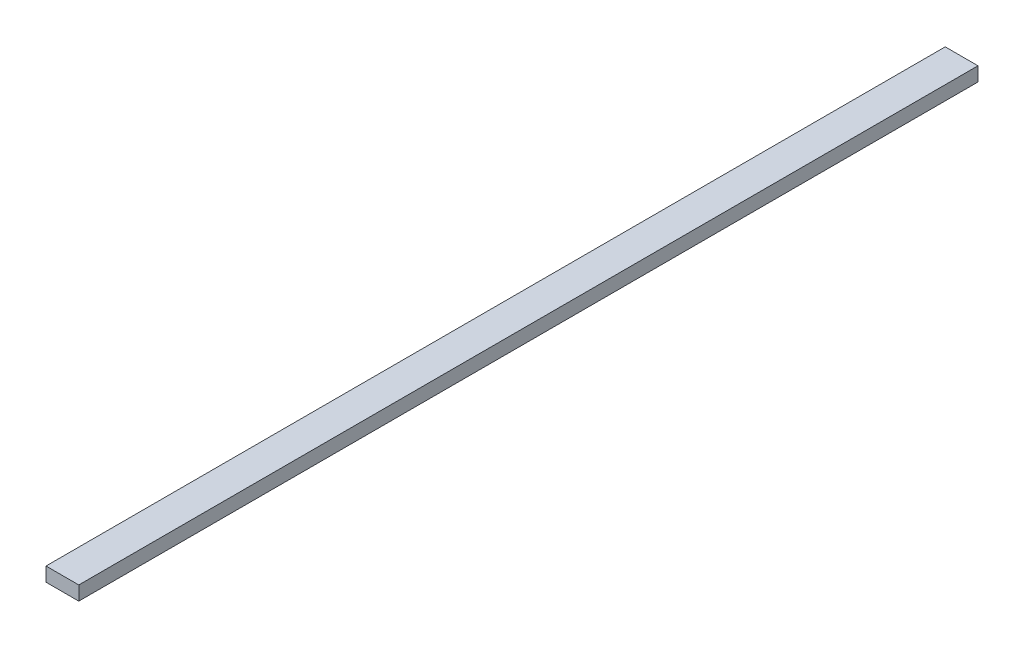
SolidWorks part; units mm, degrees
ref_plane "Front Plane" through (0, 0, 0) normal (0, 0, 1) x (1, 0, 0)
ref_plane "Top Plane" through (0, 0, 0) normal (0, 1, 0) x (1, 0, 0)
ref_plane "Right Plane" through (0, 0, 0) normal (1, 0, 0) x (0, 0, -1)
sketch "Sketch1" plane through (0, 0, 0) normal (0, 0, 1) x (1, 0, 0)
  line L1 (-44.45, -19.05) -> (44.45, -19.05)
  line L2 (-44.45, -19.05) -> (-44.45, 19.05)
  line L3 (-44.45, 19.05) -> (44.45, 19.05)
  line L4 (44.45, -19.05) -> (44.45, 19.05)
  line L5 (-44.45, -19.05) -> (44.45, 19.05) construction
  line L6 (-44.45, 19.05) -> (44.45, -19.05) construction
  point P0 (0, 0)
  dimension "D1" = 88.9
  dimension "D2" = 38.1
extrude "Boss-Extrude1" add sketch "Sketch1" along normal blind 2438.4
